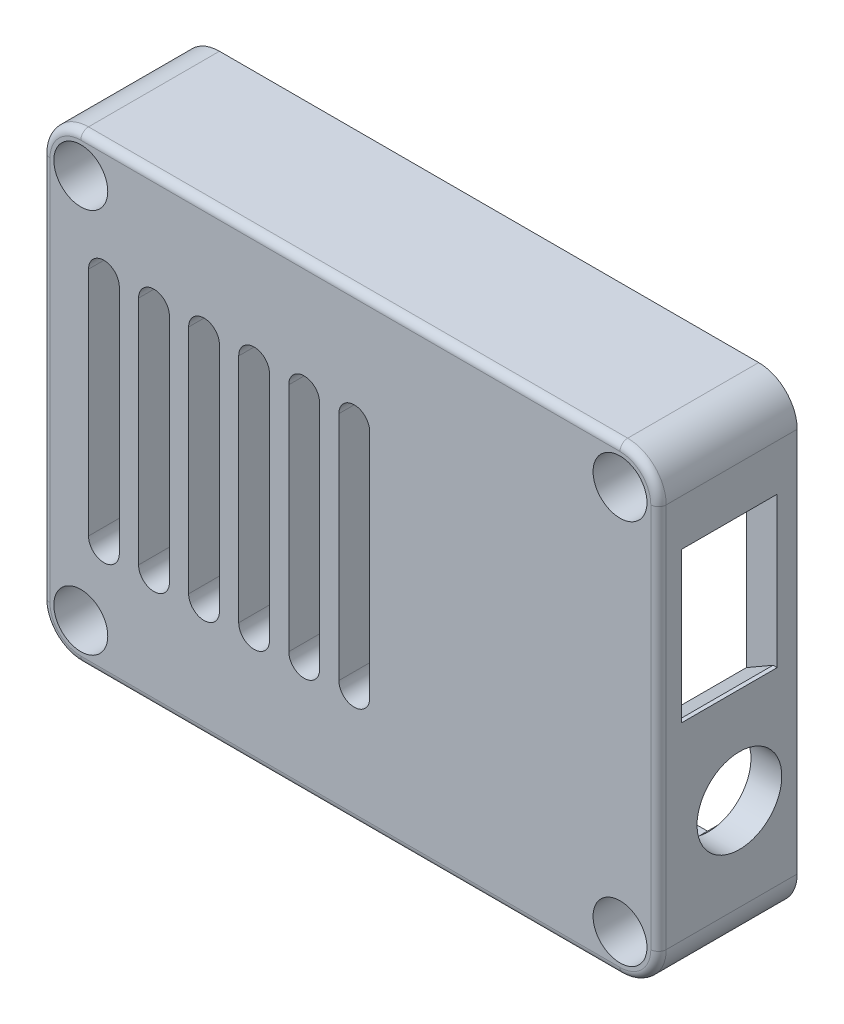
SolidWorks part; units mm, degrees
ref_plane "Front" through (0, 0, 0) normal (0, 0, 1) x (1, 0, 0)
ref_plane "Top" through (0, 0, 0) normal (0, 1, 0) x (1, 0, 0)
ref_plane "Right" through (0, 0, 0) normal (1, 0, 0) x (0, 0, -1)
sketch "Sketch1" plane through (0, 0, 0) normal (0, 0, 1) x (1, 0, 0)
  line L1 (-35, 30) -> (35, 30)
  line L2 (-40, 25) -> (-40, -25)
  line L3 (-35, -30) -> (35, -30)
  line L4 (40, 25) -> (40, -25)
  line L5 (-40, 30) -> (40, -30) construction
  line L6 (-40, -30) -> (40, 30) construction
  arc A0 (35, 30) -> (40, 25) centre (35, 25) cw
  arc A1 (40, -25) -> (35, -30) centre (35, -25) cw
  arc A2 (-35, -30) -> (-40, -25) centre (-35, -25) cw
  arc A3 (-35, 30) -> (-40, 25) centre (-35, 25) ccw
  point P0 (0, 0)
  dimension "D3" = 5
  dimension "D1" = 60
  dimension "D2" = 80
extrude "Boss-Extrude1" add sketch "Sketch1" along normal blind 18
sketch "Sketch2" plane through (0, 0, 0) normal (0, 0, -1) x (-1, 0, 0)
  line L8 (-36, 25) -> (-36, -25)
  line L9 (-35, -26) -> (35, -26)
  line L10 (36, -25) -> (36, 25)
  line L11 (35, 26) -> (-35, 26)
  line L12 (-36, 21.127) -> (-36, -21.127)
  line L13 (-31.127, -26) -> (31.127, -26)
  line L14 (36, -21.127) -> (36, 21.127)
  line L15 (31.127, 26) -> (-31.127, 26)
  arc A4 (36, -21.127) -> (31.127, -26) centre (35, -25) ccw
  arc A5 (-31.127, -26) -> (-36, -21.127) centre (-35, -25) ccw
  arc A6 (-36, 21.127) -> (-31.127, 26) centre (-35, 25) ccw
  arc A7 (31.127, 26) -> (36, 21.127) centre (35, 25) ccw
  arc A8 (-35, 26) -> (-36, 25) centre (-35, 25) ccw
  arc A9 (-36, -25) -> (-35, -26) centre (-35, -25) ccw
  arc A10 (35, -26) -> (36, -25) centre (35, -25) ccw
  arc A11 (36, 25) -> (35, 26) centre (35, 25) ccw
  dimension "D2" = 8
  dimension "D3" = 8
  dimension "D4" = 8
  dimension "D5" = 8
  dimension "D1" = 4
extrude "Cut-Extrude1" cut sketch "Sketch2" against normal offset from surface (7 mm away) 11 up to face at (0, 0, 18)
sketch "Sketch3" plane through (40, 0, 0) normal (1, 0, 0) x (0, 0, -1)
  line L0 (-8.8, 27.5) -> (-8.8, -27.5) construction
  line L3 (-18, 25) -> (0, 25) construction
  line L4 (-15, 19) -> (-2.6, 19)
  line L5 (-15, 19) -> (-15, -0.5)
  line L6 (-15, -0.5) -> (-2.6, -0.5)
  line L7 (-2.6, 19) -> (-2.6, -0.5)
  line L8 (-15, 19) -> (-2.6, -0.5) construction
  line L9 (-15, -0.5) -> (-2.6, 19) construction
  line L10 (-18, -25) -> (-18, 25) construction
  line L11 (-18, -25) -> (0, -25) construction
  line L12 (0, -25) -> (0, 25) construction
  circle A0 centre (-7.5, -13) radius 5.5
  point P6 (-8.8, 9.25)
  dimension "D5" = 11
  dimension "D6" = 12
  dimension "D1" = 12.4
  dimension "D2" = 19.5
  dimension "D3" = 6
  dimension "D4" = 9.2
  dimension "D7" = 7.5
extrude "Cut-Extrude2" cut sketch "Sketch3" against normal blind 22
sketch "Sketch4" plane through (0, 0, 7) normal (0, 0, -1) x (-1, 0, 0)
  line L6 (-31.127, -26) -> (31.127, -26) construction
  line L7 (-36, 21.127) -> (-36, -21.127) construction
  line L8 (-31.127, 26) -> (31.127, 26) construction
  line L9 (-31.127, -26) -> (-7, -26)
  line L10 (-36, 21.127) -> (-36, -21.127)
  line L11 (-31.127, 26) -> (-7, 26)
  line L12 (-7, 26) -> (-7, -26)
  line L13 (36, 21.127) -> (36, -21.127) construction
  arc A4 (-36, 21.127) -> (-31.127, 26) centre (-35, 25) ccw construction
  arc A5 (-36, 21.127) -> (-31.127, 26) centre (-35, 25) ccw
  arc A6 (-31.127, -26) -> (-36, -21.127) centre (-35, -25) ccw construction
  arc A7 (-31.127, -26) -> (-36, -21.127) centre (-35, -25) ccw
  dimension "D1" = 43
extrude "Cut-Extrude3" cut sketch "Sketch4" against normal offset from surface (8 mm away) 3 up to face at (0, 0, 18)
fillet "Fillet1" radius 1 8 edges at (40, 0, 18) (38.5355, -28.5355, 18) (0, -30, 18) (-38.5355, -28.5355, 18) (-40, 0, 18) (-38.5355, 28.5355, 18) (0, 30, 18) (38.5355, 28.5355, 18)
sketch "Sketch7" plane through (0, 0, 7) normal (0, 0, -1) x (-1, 0, 0)
  line L0 (40, 0) -> (-40, 0) construction
  line L1 (40, 25) -> (40, -25) construction
  line L2 (-40, -25) -> (-40, 25) construction
  line L3 (36, -21.127) -> (36, 21.127) construction
  line L4 (-4.5, 20.25) -> (36, 20.25)
  line L5 (-4.5, 20.25) -> (-4.5, -20.25)
  line L6 (-4.5, -20.25) -> (36, -20.25)
  line L7 (36, 20.25) -> (36, -20.25)
  line L8 (-4.5, 20.25) -> (36, -20.25) construction
  line L9 (-4.5, -20.25) -> (36, 20.25) construction
  point P6 (15.75, 0)
  dimension "D1" = 40.5
  dimension "D2" = 40.5
extrude "Cut-Extrude5" cut sketch "Sketch7" against normal blind 5
sketch "Sketch8" [suppressed] plane through (36, 0, 0) normal (-1, 0, 0) x (0, 0, 1)
  circle A0 centre (7.5, -15) radius 7
  dimension "D1" = 14
extrude "Cut-Extrude6" [suppressed] cut sketch "Sketch8" along normal blind 10
sketch "Sketch9" plane through (0, 0, 12) normal (0, 0, -1) x (-1, 0, 0)
  line L0 (-0.5, 15) -> (-0.5, -15) construction
  line L1 (1.5, 15) -> (1.5, -15)
  line L2 (-2.5, 15) -> (-2.5, -15)
  line L3 (-40, 0) -> (40, 0) construction
  line L4 (-40, -25) -> (-40, 25) construction
  line L5 (40, 25) -> (40, -25) construction
  line L6 (-4.5, 20.25) -> (-4.5, -20.25) construction
  line L7 (-33.5, 0) -> (46.5, 0) construction
  line L8 (6, 15) -> (6, -15) construction
  line L9 (8, 15) -> (8, -15)
  line L10 (4, 15) -> (4, -15)
  line L11 (-27, 0) -> (53, 0) construction
  line L12 (12.5, 15) -> (12.5, -15) construction
  line L13 (14.5, 15) -> (14.5, -15)
  line L14 (10.5, 15) -> (10.5, -15)
  line L15 (-20.5, 0) -> (59.5, 0) construction
  line L16 (19, 15) -> (19, -15) construction
  line L17 (21, 15) -> (21, -15)
  line L18 (17, 15) -> (17, -15)
  line L19 (-14, 0) -> (66, 0) construction
  line L20 (25.5, 15) -> (25.5, -15) construction
  line L21 (27.5, 15) -> (27.5, -15)
  line L22 (23.5, 15) -> (23.5, -15)
  line L23 (-7.5, 0) -> (72.5, 0) construction
  line L24 (32, 15) -> (32, -15) construction
  line L25 (34, 15) -> (34, -15)
  line L26 (30, 15) -> (30, -15)
  arc A0 (1.5, 15) -> (-2.5, 15) centre (-0.5, 15) ccw
  arc A1 (-2.5, -15) -> (1.5, -15) centre (-0.5, -15) ccw
  arc A2 (8, 15) -> (4, 15) centre (6, 15) ccw
  arc A3 (4, -15) -> (8, -15) centre (6, -15) ccw
  arc A4 (14.5, 15) -> (10.5, 15) centre (12.5, 15) ccw
  arc A5 (10.5, -15) -> (14.5, -15) centre (12.5, -15) ccw
  arc A6 (21, 15) -> (17, 15) centre (19, 15) ccw
  arc A7 (17, -15) -> (21, -15) centre (19, -15) ccw
  arc A8 (27.5, 15) -> (23.5, 15) centre (25.5, 15) ccw
  arc A9 (23.5, -15) -> (27.5, -15) centre (25.5, -15) ccw
  arc A10 (34, 15) -> (30, 15) centre (32, 15) ccw
  arc A11 (30, -15) -> (34, -15) centre (32, -15) ccw
  point P2 (-0.5, 0)
  point P19 (6, 0)
  point P28 (12.5, 0)
  point P37 (19, 0)
  point P46 (25.5, 0)
  point P55 (32, 0)
  dimension "D1" = 2
  dimension "D2" = 30
  dimension "D3" = 2
  dimension "D4" = 6
extrude "Cut-Extrude7" cut sketch "Sketch9" against normal through all
sketch "Sketch10" plane through (0, 0, 18) normal (0, 0, 1) x (1, 0, 0)
  line L0 (-40, -25) -> (-40, 25) construction
  line L1 (35, -30) -> (-35, -30) construction
  line L2 (-35, 30) -> (35, 30) construction
  line L3 (40, 25) -> (40, -25) construction
  circle A0 centre (-35, 25) radius 3.5
  circle A1 centre (-35, -25) radius 3.5
  circle A2 centre (35, -25) radius 3.5
  circle A3 centre (35, 25) radius 3.5
  dimension "D1" = 7
  dimension "D2" = 7
  dimension "D3" = 7
  dimension "D4" = 7
  dimension "D5" = 5
  dimension "D6" = 5
  dimension "D7" = 5
  dimension "D8" = 5
  dimension "D9" = 5
  dimension "D10" = 5
  dimension "D11" = 5
  dimension "D12" = 5
extrude "Cut-Extrude8" cut sketch "Sketch10" against normal offset from surface (14 mm away) 4 up to face at (0, 0, 0)
sketch "Sketch11" plane through (0, 0, 4) normal (0, 0, 1) x (1, 0, 0)
  circle A0 centre (35, -25) radius 1.85
  circle A1 centre (35, 25) radius 1.85
  circle A2 centre (-35, 25) radius 1.85
  circle A3 centre (-35, -25) radius 1.85
  dimension "D1" = 3.7
  dimension "D2" = 3.7
  dimension "D3" = 3.7
  dimension "D4" = 3.7
extrude "Cut-Extrude9" cut sketch "Sketch11" against normal through all
chamfer "Chamfer1" distance 2 angle 60 2 edges at (36, -0.5, 8.8) (36, 19, 8.8)
